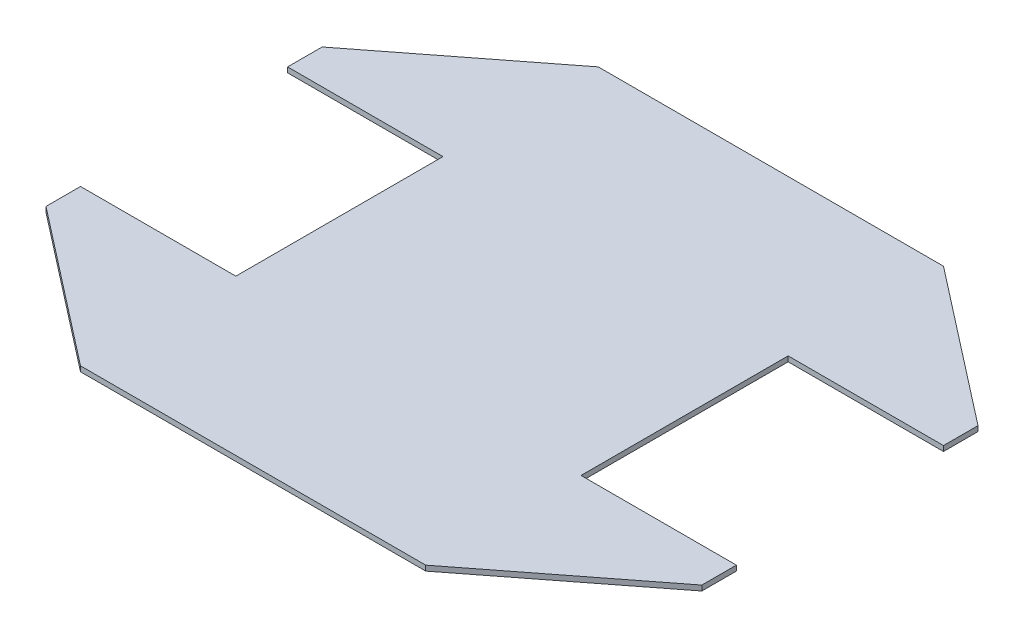
SolidWorks part; units mm, degrees
ref_plane "Front Plane" through (0, 0, 0) normal (0, 0, 1) x (1, 0, 0)
ref_plane "Top Plane" through (0, 0, 0) normal (0, 1, 0) x (1, 0, 0)
ref_plane "Right Plane" through (0, 0, 0) normal (1, 0, 0) x (0, 0, -1)
sketch "Sketch1" plane through (0, 0, 0) normal (0, 1, 0) x (1, 0, 0)
  line L0 (-100, 150) -> (100, 150)
  line L1 (100, 150) -> (190, 80)
  line L2 (190, 80) -> (190, 60)
  line L3 (190, 60) -> (100, 60)
  line L4 (100, 60) -> (100, -60)
  line L5 (100, -60) -> (190, -60)
  line L6 (190, -60) -> (190, -80)
  line L7 (190, -80) -> (100, -150)
  line L8 (100, -150) -> (-100, -150)
  line L9 (-100, -150) -> (-190, -80)
  line L10 (-190, -80) -> (-190, -60)
  line L11 (-190, -60) -> (-100, -60)
  line L12 (-100, -60) -> (-100, 60)
  line L13 (-100, 60) -> (-190, 60)
  line L14 (-190, 60) -> (-190, 80)
  line L15 (-190, 80) -> (-100, 150)
  point P12 (145, -60)
  point P18 (-190, 70)
  point P19 (190, 70)
  point P20 (-190, -70)
  point P21 (190, -70)
  dimension "D1" = 200
  dimension "D2" = 300
  dimension "D3" = 200
  dimension "D4" = 120
  dimension "D5" = 20
  dimension "D6" = 20
  dimension "D7" = 90
  dimension "D8" = 150
  dimension "D9" = 90
  dimension "D10" = 20
  dimension "D11" = 120
  dimension "D12" = 20
  dimension "D13" = 200
  dimension "D14" = 100
  dimension "D15" = 380
  dimension "D16" = 380
  dimension "D17" = 90
  dimension "D18" = 90
  dimension "D19" = 90
extrude "Boss-Extrude1" add sketch "Sketch1" along normal blind 3
